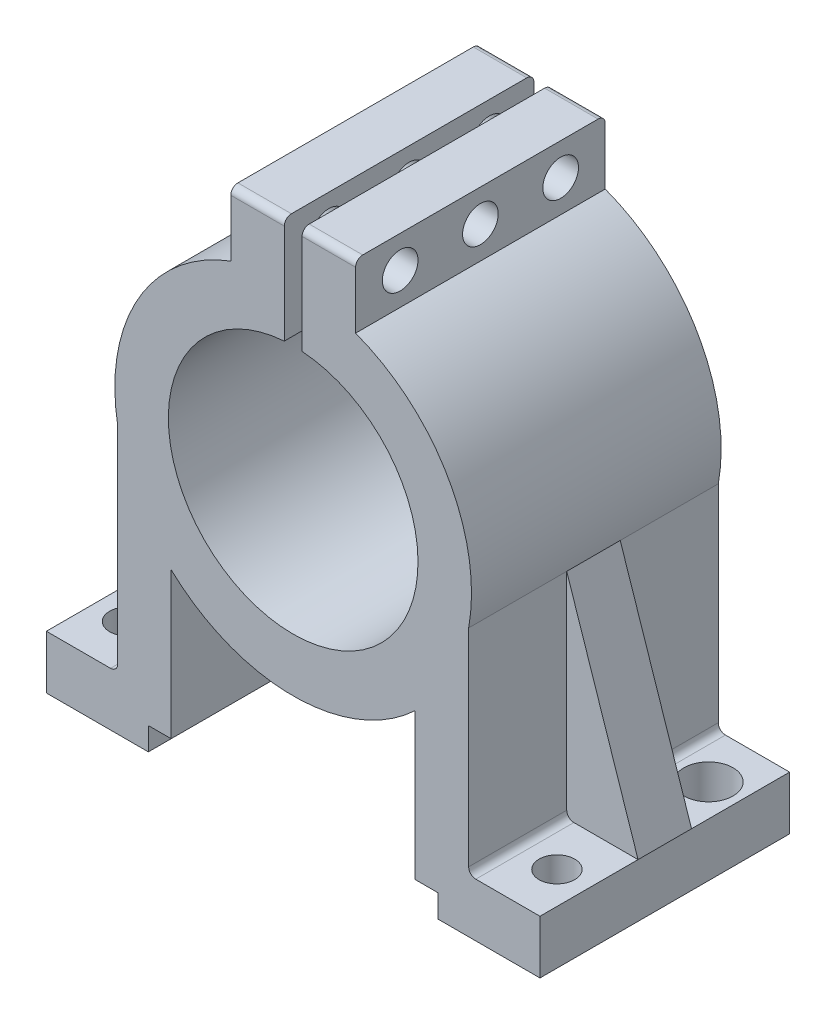
SolidWorks part; units mm, degrees
ref_plane "Front Plane" through (0, 0, 0) normal (0, 0, 1) x (1, 0, 0)
ref_plane "Top Plane" through (0, 0, 0) normal (0, 1, 0) x (1, 0, 0)
ref_plane "Right Plane" through (0, 0, 0) normal (1, 0, 0) x (0, 0, -1)
sketch "Sketch1" plane through (0, 0, 0) normal (0, 0, 1) x (1, 0, 0)
  line L0 (0, 20) -> (0, 14)
  line L1 (0, -14) -> (0, -20)
  line L2 (27.6812, -33.5567) -> (27.6812, -27.5567)
  line L3 (27.6812, -33.5567) -> (16.2412, -33.5567)
  line L4 (16.2412, -33.5567) -> (16.2412, -30.9967)
  line L5 (16.2412, -30.9967) -> (13.6812, -30.9967)
  line L6 (13.6812, -30.9967) -> (13.6812, -14.5885)
  line L7 (27.6812, -27.5567) -> (20.4812, -27.5567)
  line L8 (19.6812, -26.7567) -> (19.6812, -3.5567)
  line L9 (0, 20) -> (0, 25.935)
  line L10 (0, 25.935) -> (7, 25.935)
  line L11 (7, 25.935) -> (7, 18.735)
  arc A0 (0, -20) -> (13.6812, -14.5885) centre (0, 0) ccw
  arc A1 (0, -14) -> (0, 14) centre (0, 0) ccw
  arc A2 (20.4812, -27.5567) -> (19.6812, -26.7567) centre (20.4812, -26.7567) cw
  arc A3 (19.6812, -3.5567) -> (7, 18.735) centre (0, 0) ccw
  point P16 (19.6812, -27.5567)
  point P17 (0, 0)
  point P21 (0, 0)
  dimension "D1" = 40
  dimension "D2" = 28
  dimension "D6" = 0.8
  dimension "D3" = 2.56
  dimension "D4" = 14
  dimension "D5" = 8
  dimension "D7" = 6
  dimension "D8" = 2.56
  dimension "D9" = 24
  dimension "D10" = 7.2
  dimension "D11" = 7
extrude "Boss-Extrude1" add sketch "Sketch1" along normal blind 28
sketch "Sketch2" plane through (0, 0, 0) normal (0, 0, 1) x (1, 0, 0)
  line L0 (19.6812, -26.7567) -> (19.6812, -3.5567) construction
  line L1 (19.6812, -26.7567) -> (19.6812, -3.5567)
  line L2 (27.6812, -27.5567) -> (20.4812, -27.5567)
  line L3 (27.6812, -27.5567) -> (20.4812, -27.5567)
  line L4 (19.6812, -3.5567) -> (27.6812, -27.5567)
  line L5 (20.4812, -27.5567) -> (19.6812, -27.5567)
  line L6 (19.6812, -26.7567) -> (19.6812, -27.5567)
extrude "Boss-Extrude2" add sketch "Sketch2" along normal blind 6 from offset 11
sketch "Sketch3" plane through (7, 0, 0) normal (1, 0, 0) x (0, 0, -1)
  line L0 (-14, 25.935) -> (-14, 18.735) construction
  line L1 (-28, 25.935) -> (0, 25.935) construction
  line L2 (-28, 18.735) -> (0, 18.735) construction
  circle A0 centre (-23, 22.335) radius 2
  circle A1 centre (-14, 22.335) radius 2
  circle A2 centre (-5, 22.335) radius 2
  point P12 (0, 0)
  point P13 (-14, 22.335)
  point P14 (0, 0)
  point P15 (0, 0)
  dimension "D1" = 4
  dimension "D2" = 9
  dimension "D3" = 9
extrude "Cut-Extrude1" cut sketch "Sketch3" against normal up to next
fillet "Fillet1" radius 0.8 2 edges at (3.5, 25.935, 0) (3.5, 25.935, 28)
sketch "Sketch4" plane through (0, -27.5567, 0) normal (0, 1, 0) x (1, 0, 0)
  line L0 (24.0812, -28) -> (24.0812, -20.5) construction
  line L1 (27.6812, -28) -> (20.4812, -28) construction
  line L2 (27.6812, 0) -> (20.4812, 0) construction
  line L3 (20.4812, -22.5) -> (27.6812, -22.5) construction
  line L4 (20.4812, -28) -> (20.4812, -17) construction
  line L5 (27.6812, -28) -> (27.6812, -17) construction
  line L7 (20.4812, -11) -> (20.4812, 0) construction
  line L8 (20.4812, -5.5) -> (27.6812, -5.5) construction
  line L9 (27.6812, -11) -> (27.6812, 0) construction
  line L10 (24.0812, -8.25) -> (24.0812, 0) construction
  circle A0 centre (24.0812, -22.5) radius 2
  circle A1 centre (24.0812, -5.5) radius 2.75
  point P16 (0, 0)
  point P23 (0, 0)
  point P24 (0, 0)
  point P25 (0, 0)
  point P26 (24.0812, -5.5)
  point P29 (0, 0)
  dimension "D1" = 4
  dimension "D2" = 5.5
extrude "Cut-Extrude2" cut sketch "Sketch4" against normal through all
sketch "Sketch5" plane through (0, 0, 0) normal (0, 0, 1) x (1, 0, 0)
  line L0 (0, -14) -> (0, 14) construction
  line L1 (0, -14) -> (0, -20) construction
  arc A0 (0, -14) -> (0, 14) centre (0, 0) ccw construction
mirror "Mirror1" about plane through (0, 0, 0) normal (1, 0, 0) of "Cut-Extrude2", "Fillet1", "Cut-Extrude1", "Boss-Extrude2", "Boss-Extrude1"
sketch "Sketch6" plane through (0, 0, 28) normal (0, 0, 1) x (1, 0, 0)
  line L2 (-1, 41.8136) -> (1, 41.8136)
  line L3 (-1, 41.8136) -> (-1, 8.4564)
  line L4 (-1, 8.4564) -> (1, 8.4564)
  line L5 (1, 41.8136) -> (1, 8.4564)
  line L6 (-1, 41.8136) -> (1, 8.4564) construction
  line L7 (-1, 8.4564) -> (1, 41.8136) construction
  line L18 (7, 25.135) -> (0, 25.135)
  line L19 (0, 25.135) -> (-7, 25.135)
  line L20 (-7, 25.135) -> (-7, 18.735)
  line L21 (-19.6812, -3.5567) -> (-19.6812, -26.7567)
  line L22 (-20.4812, -27.5567) -> (-27.6812, -27.5567)
  line L23 (-27.6812, -27.5567) -> (-27.6812, -33.5567)
  line L24 (-27.6812, -33.5567) -> (-16.2412, -33.5567)
  line L25 (-16.2412, -33.5567) -> (-16.2412, -30.9967)
  line L26 (-16.2412, -30.9967) -> (-13.6812, -30.9967)
  line L27 (-13.6812, -30.9967) -> (-13.6812, -14.5885)
  line L28 (13.6812, -14.5885) -> (13.6812, -30.9967)
  line L29 (13.6812, -30.9967) -> (16.2412, -30.9967)
  line L30 (16.2412, -30.9967) -> (16.2412, -33.5567)
  line L31 (16.2412, -33.5567) -> (27.6812, -33.5567)
  line L32 (27.6812, -33.5567) -> (27.6812, -27.5567)
  line L33 (27.6812, -27.5567) -> (20.4812, -27.5567)
  line L34 (19.6812, -26.7567) -> (19.6812, -3.5567)
  line L35 (7, 18.735) -> (7, 25.135)
  line L36 (7, 25.135) -> (0, 25.135)
  line L37 (0, 25.135) -> (-7, 25.135)
  line L38 (-7, 25.135) -> (-7, 18.735)
  line L39 (-19.6812, -3.5567) -> (-19.6812, -26.7567)
  line L40 (-20.4812, -27.5567) -> (-27.6812, -27.5567)
  line L41 (-27.6812, -27.5567) -> (-27.6812, -33.5567)
  line L42 (-27.6812, -33.5567) -> (-16.2412, -33.5567)
  line L43 (-16.2412, -33.5567) -> (-16.2412, -30.9967)
  line L44 (-16.2412, -30.9967) -> (-13.6812, -30.9967)
  line L45 (-13.6812, -30.9967) -> (-13.6812, -14.5885)
  line L46 (13.6812, -14.5885) -> (13.6812, -30.9967)
  line L47 (13.6812, -30.9967) -> (16.2412, -30.9967)
  line L48 (16.2412, -30.9967) -> (16.2412, -33.5567)
  line L49 (16.2412, -33.5567) -> (27.6812, -33.5567)
  line L50 (27.6812, -33.5567) -> (27.6812, -27.5567)
  line L51 (27.6812, -27.5567) -> (20.4812, -27.5567)
  line L52 (19.6812, -26.7567) -> (19.6812, -3.5567)
  line L53 (7, 18.735) -> (7, 25.135)
  arc A5 (-7, 18.735) -> (-19.6812, -3.5567) centre (0, 0) ccw
  arc A6 (-20.4812, -27.5567) -> (-19.6812, -26.7567) centre (-20.4812, -26.7567) ccw
  arc A7 (-13.6812, -14.5885) -> (13.6812, -14.5885) centre (0, 0) ccw
  arc A8 (19.6812, -26.7567) -> (20.4812, -27.5567) centre (20.4812, -26.7567) ccw
  arc A9 (19.6812, -3.5567) -> (7, 18.735) centre (0, 0) ccw
  arc A10 (-7, 18.735) -> (-19.6812, -3.5567) centre (0, 0) ccw
  arc A11 (-20.4812, -27.5567) -> (-19.6812, -26.7567) centre (-20.4812, -26.7567) ccw
  arc A12 (-13.6812, -14.5885) -> (13.6812, -14.5885) centre (0, 0) ccw
  arc A13 (19.6812, -26.7567) -> (20.4812, -27.5567) centre (20.4812, -26.7567) ccw
  arc A14 (19.6812, -3.5567) -> (7, 18.735) centre (0, 0) ccw
  circle M25 centre (0, 0) radius 14
  line M26 (7, 25.135) -> (0, 25.135)
  line M27 (0, 25.135) -> (-7, 25.135)
  dimension "D2" = 2
  dimension "D1" = 0
extrude "Cut-Extrude3" cut sketch "Sketch6" against normal through all contours L5 L3 L4 M25 | L5 L3 M26 M27 M25 | L5 L2 L3 M27 M26
